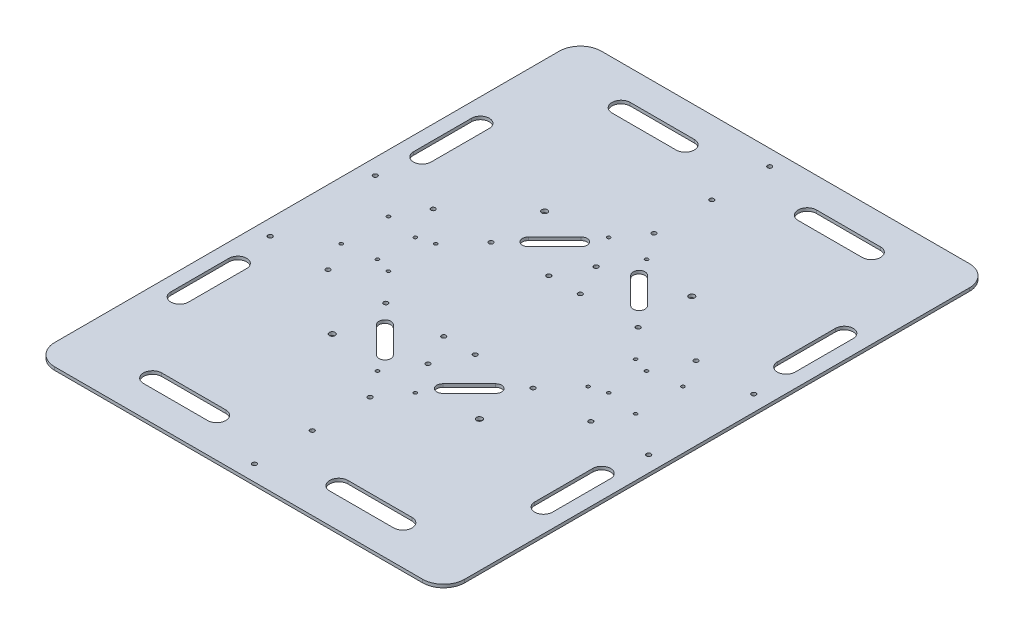
SolidWorks part; units mm, degrees
material "A-玻璃纤维"
ref_plane "前视基准面" through (0, 0, 0) normal (0, 0, 1) x (1, 0, 0)
ref_plane "上视基准面" through (0, 0, 0) normal (0, 1, 0) x (1, 0, 0)
ref_plane "右视基准面" through (0, 0, 0) normal (1, 0, 0) x (0, 0, -1)
sketch "草图2" plane through (0, 0, 0) normal (0, 1, 0) x (1, 0, 0)
  line L1 (-195, -260) -> (195, -260)
  line L2 (-195, -260) -> (-195, 260)
  line L3 (-195, 260) -> (195, 260)
  line L4 (195, -260) -> (195, 260)
  line L5 (-195, -260) -> (195, 260) construction
  line L6 (-195, 260) -> (195, -260) construction
  point P0 (0, 0)
  dimension "D1" = 390
  dimension "D2" = 520
extrude "凸台-拉伸1" add sketch "草图2" along normal blind 3
fillet "圆角1" radius 20 4 edges at (-195, 1.5, -260) (195, 1.5, -260) (195, 1.5, 260) (-195, 1.5, 260)
ref_plane "基准面1" through (0, 0, 0) normal (1, 0, 0) x (0, 0, -1)
ref_plane "基准面2" through (0, 0, 0) normal (0, 0, -1) x (-1, 0, 0)
sketch "草图9" plane through (0, 3, 0) normal (0, 1, 0) x (1, 0, 0)
  line L0 (1.65, 0) -> (-1.65, 0) construction
  line L1 (0, -1.65) -> (0, 1.65) construction
  circle A0 centre (15, 50) radius 2.1
  dimension "D1" = 4.2
  dimension "D2" = 50
  dimension "D3" = 15
extrude "切除-拉伸3" cut sketch "草图9" against normal blind 10
pattern_linear "阵列(线性)3" count 4 spacing 55 along (1, 0, 0) of "切除-拉伸3"
mirror "镜向2" about plane through (0, 0, 0) normal (1, 0, 0) of "阵列(线性)3", "切除-拉伸3"
mirror "镜向3" about plane through (0, 0, 0) normal (0, 0, -1) of "镜向2", "切除-拉伸3", "阵列(线性)3"
sketch "草图11" plane through (0, 3, 0) normal (0, 1, 0) x (1, 0, 0)
  line L1 (-175, -260) -> (175, -260) construction
  line L2 (-195, 240) -> (-195, -240) construction
  circle A0 centre (0.05, -245) radius 2.1
  dimension "D1" = 4.2
  dimension "D2" = 15
  dimension "D3" = 195.05
extrude "切除-拉伸4" cut sketch "草图11" against normal through all
pattern_linear "阵列(线性)4" count 4 spacing 55 along (0, 0, -1) of "切除-拉伸4"
mirror "镜向4" about plane through (0, 0, 0) normal (0, 0, -1) of "阵列(线性)4", "切除-拉伸4"
sketch "草图15" plane through (0, 3, 0) normal (0, 1, 0) x (1, 0, 0)
  line L0 (173.0685, 87.7409) -> (173.0685, 143.006) construction
  line L3 (164.6399, 87.7409) -> (164.6399, 143.006)
  line L4 (181.497, 87.7409) -> (181.497, 143.006)
  arc A2 (164.6399, 87.7409) -> (181.497, 87.7409) centre (173.0685, 87.7409) ccw
  arc A3 (181.497, 143.006) -> (164.6399, 143.006) centre (173.0685, 143.006) ccw
  point P2 (173.0685, 115.3734)
extrude "切除-拉伸6" cut sketch "草图15" against normal through all
mirror "镜向10" about plane through (0, 0, 0) normal (1, 0, 0) of "切除-拉伸6"
mirror "镜向11" about plane through (0, 0, 0) normal (0, 0, -1) of "镜向10", "切除-拉伸6"
sketch "草图16" plane through (0, 3, 0) normal (0, 1, 0) x (1, 0, 0)
  line L0 (1.65, 0) -> (-1.65, 0) construction
  line L1 (195, -240) -> (195, 240) construction
  circle A0 centre (140, 22.5) radius 1.6
  dimension "D1" = 3.2
  dimension "D2" = 22.5
  dimension "D3" = 55
extrude "切除-拉伸7" cut sketch "草图16" against normal through all
pattern_linear "阵列(线性)5" count 2 spacing 45 along (-1, 0, 0) of "切除-拉伸7"
mirror "镜向12" about plane through (0, 0, 0) normal (0, 0, -1) of "阵列(线性)5", "切除-拉伸7"
mirror "镜向13" about plane through (0, 0, 0) normal (1, 0, 0) of "镜向12", "切除-拉伸7", "阵列(线性)5"
sketch "草图17" plane through (0, 3, 0) normal (0, 1, 0) x (1, 0, 0)
  line L0 (27.5202, 93.3587) -> (52.6676, 68.2113) construction
  line L1 (31.5043, 97.3428) -> (56.6517, 72.1954)
  line L2 (23.5361, 89.3746) -> (48.6834, 64.2272)
  arc A0 (31.5043, 97.3428) -> (23.5361, 89.3746) centre (27.5202, 93.3587) ccw
  arc A1 (48.6834, 64.2272) -> (56.6517, 72.1954) centre (52.6676, 68.2113) ccw
  point P2 (40.0939, 80.785)
extrude "切除-拉伸13" cut sketch "草图17" against normal blind 10
mirror "镜向14" about plane through (0, 0, 0) normal (0, 0, -1) of "切除-拉伸13"
mirror "镜向15" about plane through (0, 0, 0) normal (1, 0, 0) of "镜向14", "切除-拉伸13"
sketch "草图18" plane through (0, 3, 0) normal (0, 1, 0) x (1, 0, 0)
  line L0 (-195, 240) -> (-195, -240) construction
  circle A0 centre (-70, 101) radius 2.75
  circle A1 centre (-70, 50) radius 2.1 construction
  dimension "D1" = 5.5
  dimension "D2" = 51
  dimension "D3" = 125
extrude "切除-拉伸14" cut sketch "草图18" against normal through all
mirror "镜向16" about plane through (0, 0, 0) normal (0, 0, -1) of "切除-拉伸14"
mirror "镜向17" about plane through (0, 0, 0) normal (1, 0, 0) of "镜向16", "切除-拉伸14"
sketch "草图19" plane through (0, 3, 0) normal (0, 1, 0) x (1, 0, 0)
  line L0 (119.034, -222.8057) -> (58.0592, -222.8057) construction
  line L3 (119.034, -231.5021) -> (58.0592, -231.5021)
  line L4 (119.034, -214.1093) -> (58.0592, -214.1093)
  arc A2 (119.034, -231.5021) -> (119.034, -214.1093) centre (119.034, -222.8057) ccw
  arc A3 (58.0592, -214.1093) -> (58.0592, -231.5021) centre (58.0592, -222.8057) ccw
  point P2 (88.5466, -222.8057)
extrude "切除-拉伸15" cut sketch "草图19" against normal through all
mirror "镜向18" about plane through (0, 0, 0) normal (1, 0, 0) of "切除-拉伸15"
mirror "镜向19" about plane through (0, 0, 0) normal (0, 0, -1) of "镜向18", "切除-拉伸15"
sketch "草图20" plane through (0, 0, 0) normal (0, -1, 0) x (1, 0, 0)
  line L0 (175, -260) -> (-175, -260) construction
  line L1 (0, -1.65) -> (0, 1.65) construction
  circle A0 centre (-18, -110) radius 1.6
  point P2 (0, 0)
  dimension "D1" = 3.2
  dimension "D2" = 150
  dimension "D3" = 18
extrude "切除-拉伸16" cut sketch "草图20" against normal through all
mirror "镜向20" about plane through (0, 0, 0) normal (1, 0, 0) of "切除-拉伸16"
mirror "镜向21" about plane through (0, 0, 0) normal (0, 0, -1) of "镜向20", "切除-拉伸16"
sketch "草图21" plane through (0, 0, 0) normal (0, -1, 0) x (-1, 0, 0)
  line L0 (0, 1.65) -> (0, -1.65) construction
  line L1 (1.65, 0) -> (-1.65, 0) construction
  circle A0 centre (110, 18) radius 1.6
  dimension "D1" = 3.2
  dimension "D2" = 110
  dimension "D3" = 18
extrude "切除-拉伸17" cut sketch "草图21" against normal through all
mirror "镜向22" about plane through (0, 0, 0) normal (0, 0, -1) of "切除-拉伸17"
mirror "镜向23" about plane through (0, 0, 0) normal (1, 0, 0) of "镜向22", "切除-拉伸17"
